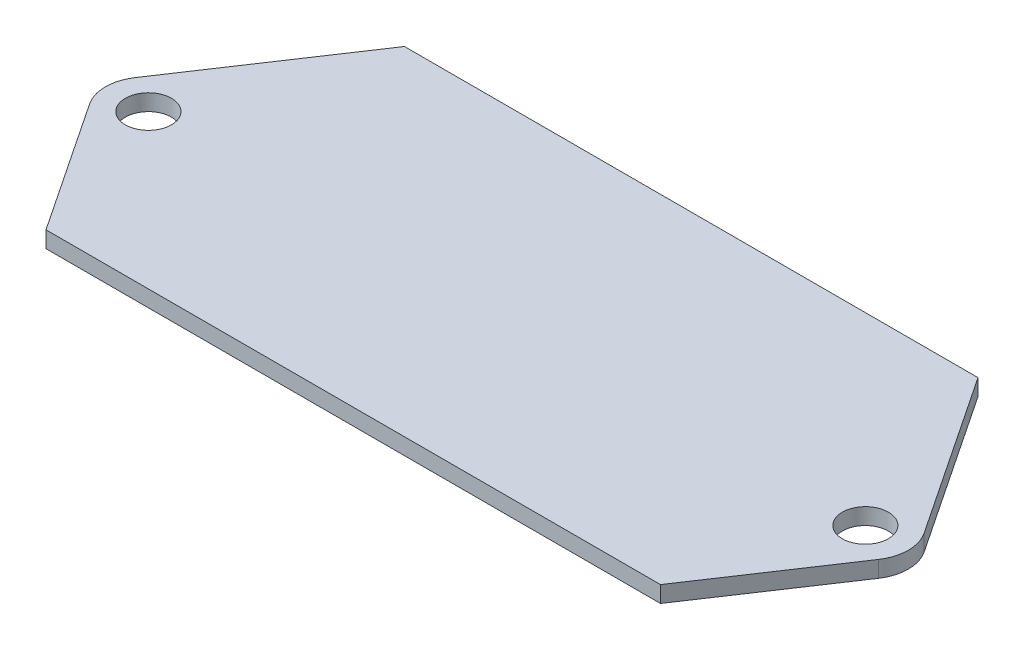
SolidWorks part; units mm, degrees
ref_plane "Front Plane" through (0, 0, 0) normal (0, 0, 1) x (1, 0, 0)
ref_plane "Top Plane" through (0, 0, 0) normal (0, 1, 0) x (1, 0, 0)
ref_plane "Right Plane" through (0, 0, 0) normal (1, 0, 0) x (0, 0, -1)
sketch "Sketch1" plane through (0, 0, 0) normal (0, 1, 0) x (1, 0, 0)
  line L0 (0, 15) -> (10, 0)
  line L1 (0, 0) -> (80, 0)
  line L2 (0, 0) -> (0, 33)
  line L3 (0, 33) -> (80, 33)
  line L4 (80, 0) -> (80, 33)
  line L5 (0, 15) -> (12, 33)
  line L6 (70, 0) -> (80, 15)
  line L7 (80, 15) -> (68, 33)
  circle A0 centre (5, 15) radius 2.25
  circle A1 centre (75, 15) radius 2.25
  dimension "D5" = 4.5
  dimension "D6" = 4.5
  dimension "D1" = 80
  dimension "D2" = 33
  dimension "D3" = 10
  dimension "D4" = 10
  dimension "D7" = 5
  dimension "D8" = 5
  dimension "D9" = 2
  dimension "D10" = 15
  dimension "D11" = 2
  dimension "D12" = 15
  dimension "D13" = 15
  dimension "D14" = 15
extrude "Boss-Extrude1" add sketch "Sketch1" along normal blind 1.6 contours L6 L7 L3 L5 L0 L1 A1 A0
fillet "Fillet1" radius 4 2 edges at (80, 0.8, -15) (0, 0.8, -15)
